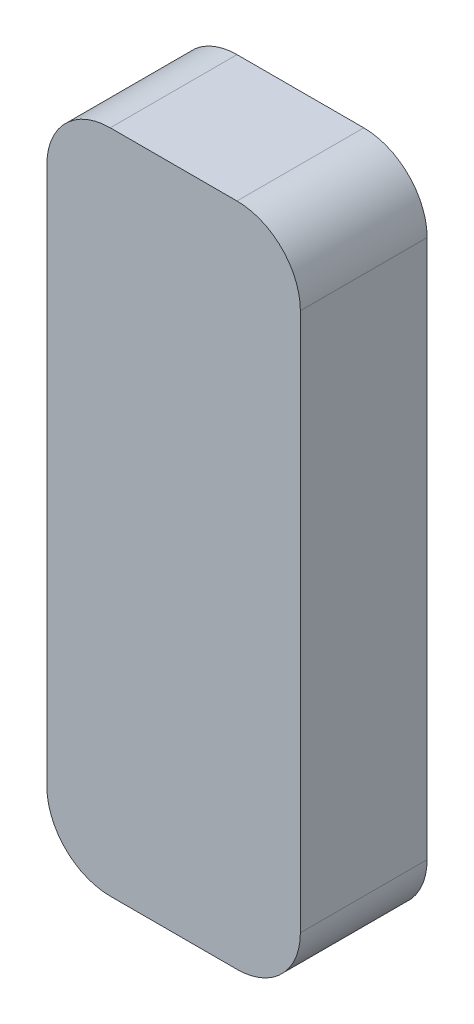
SolidWorks part; units mm, degrees
ref_plane "前视基准面" through (0, 0, 0) normal (0, 0, 1) x (1, 0, 0)
ref_plane "上视基准面" through (0, 0, 0) normal (0, 1, 0) x (1, 0, 0)
ref_plane "右视基准面" through (0, 0, 0) normal (1, 0, 0) x (0, 0, -1)
sketch "草图1" plane through (0, 0, 0) normal (0, 0, 1) x (1, 0, 0)
  line L1 (-10, -52.5) -> (10, -52.5)
  line L2 (-20, -42.5) -> (-20, 42.5)
  line L3 (-10, 52.5) -> (10, 52.5)
  line L4 (20, -42.5) -> (20, 42.5)
  line L5 (-20, -52.5) -> (20, 52.5) construction
  line L6 (-20, 52.5) -> (20, -52.5) construction
  arc A0 (10, -52.5) -> (20, -42.5) centre (10, -42.5) ccw
  arc A1 (-20, 42.5) -> (-10, 52.5) centre (-10, 42.5) cw
  arc A2 (-10, -52.5) -> (-20, -42.5) centre (-10, -42.5) cw
  arc A3 (10, 52.5) -> (20, 42.5) centre (10, 42.5) cw
  point P0 (0, 0)
  dimension "D3" = 10
  dimension "D1" = 105
  dimension "D2" = 40
extrude "凸台-拉伸1" add sketch "草图1" along normal blind 20
